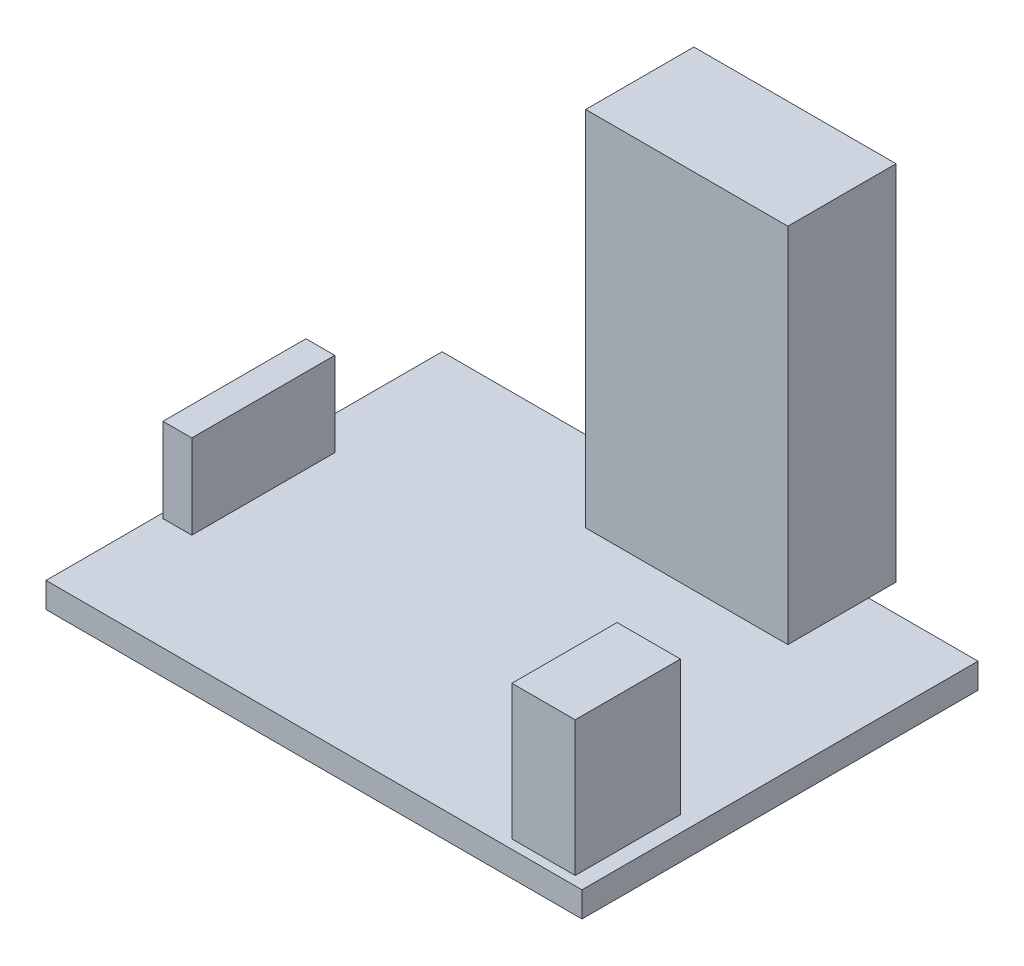
SolidWorks part; units mm, degrees
ref_plane "Front Plane" through (0, 0, 0) normal (0, 0, 1) x (1, 0, 0)
ref_plane "Top Plane" through (0, 0, 0) normal (0, 1, 0) x (1, 0, 0)
ref_plane "Right Plane" through (0, 0, 0) normal (1, 0, 0) x (0, 0, -1)
sketch "Sketch1" plane through (0, 0, 0) normal (0, 1, 0) x (1, 0, 0)
  line L1 (0, 0) -> (31.8, 0)
  line L2 (0, 0) -> (0, -23.5)
  line L3 (0, -23.5) -> (31.8, -23.5)
  line L4 (31.8, 0) -> (31.8, -23.5)
  dimension "D1" = 31.8
  dimension "D2" = 23.5
extrude "Boss-Extrude1" add sketch "Sketch1" along normal blind 1.5
sketch "Sketch2" plane through (0, 1.5, 0) normal (0, 1, 0) x (1, 0, 0)
  line L1 (0.2931, -8.3676) -> (2.0037, -8.3676)
  line L2 (0.2931, -8.3676) -> (0.2931, -16.8543)
  line L3 (0.2931, -16.8543) -> (2.0037, -16.8543)
  line L4 (2.0037, -8.3676) -> (2.0037, -16.8543)
extrude "Boss-Extrude2" add sketch "Sketch2" along normal blind 5
sketch "Sketch3" plane through (0, 1.5, 0) normal (0, 1, 0) x (1, 0, 0)
  line L1 (30.8627, -16.721) -> (27.1082, -16.721)
  line L2 (30.8627, -16.721) -> (30.8627, -22.9638)
  line L3 (30.8627, -22.9638) -> (27.1082, -22.9638)
  line L4 (27.1082, -16.721) -> (27.1082, -22.9638)
extrude "Boss-Extrude3" add sketch "Sketch3" along normal blind 8
sketch "Sketch4" plane through (0, 1.5, 0) normal (0, 1, 0) x (1, 0, 0)
  line L1 (13.3118, -4.7908) -> (25.3086, -4.7908)
  line L2 (13.3118, -4.7908) -> (13.3118, 1.6297)
  line L3 (13.3118, 1.6297) -> (25.3086, 1.6297)
  line L4 (25.3086, -4.7908) -> (25.3086, 1.6297)
extrude "Boss-Extrude4" add sketch "Sketch4" along normal blind 21.5
